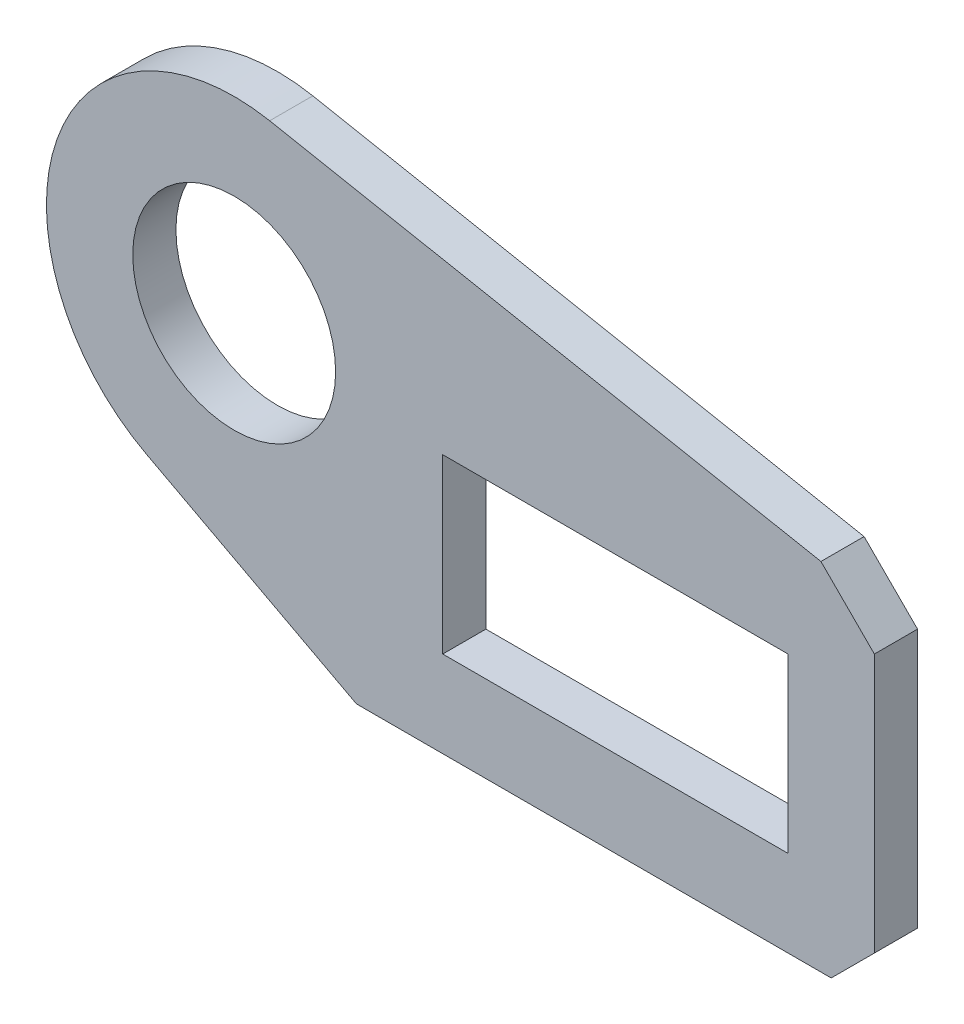
SolidWorks part; units mm, degrees
ref_plane "Plan de face" through (0, 0, 0) normal (0, 0, 1) x (1, 0, 0)
ref_plane "Plan de dessus" through (0, 0, 0) normal (0, 1, 0) x (1, 0, 0)
ref_plane "Plan de droite" through (0, 0, 0) normal (1, 0, 0) x (0, 0, -1)
sketch "Esquisse1" plane through (0, 0, 0) normal (0, 0, 1) x (1, 0, 0)
  line L0 (60, 20) -> (60, 0) construction
  line L1 (0, 0) -> (120, 0)
  line L2 (0, 0) -> (0, 80) construction
  line L3 (0, 80) -> (120, 80) construction
  line L4 (120, 0) -> (120, 80)
  line L5 (20, 60) -> (100, 60)
  line L6 (20, 60) -> (20, 20)
  line L7 (20, 20) -> (100, 20)
  line L8 (100, 60) -> (100, 20)
  line L9 (-20.1, 106.9442) -> (120, 80)
  line L10 (-48.6788, 25.7877) -> (0, 0)
  line L11 (-28.3154, 64.2271) -> (20, 60) construction
  circle A0 centre (-28.3154, 64.2271) radius 23.5
  arc A1 (-20.1, 106.9442) -> (-48.6788, 25.7877) centre (-28.3154, 64.2271) ccw
  dimension "D6" = 47
  dimension "D8" = 48.5
  dimension "D7" = 43.5
  dimension "D1" = 80
  dimension "D2" = 40
  dimension "D3" = 20
  dimension "D4" = 20
  dimension "D5" = 20
  dimension "D9" = 5
extrude "Boss.-Extru.1" add sketch "Esquisse1" along normal blind 10
chamfer "Chanfrein1" distance 10 angle 45 2 edges at (120, 80, 5) (120, 0, 5)
